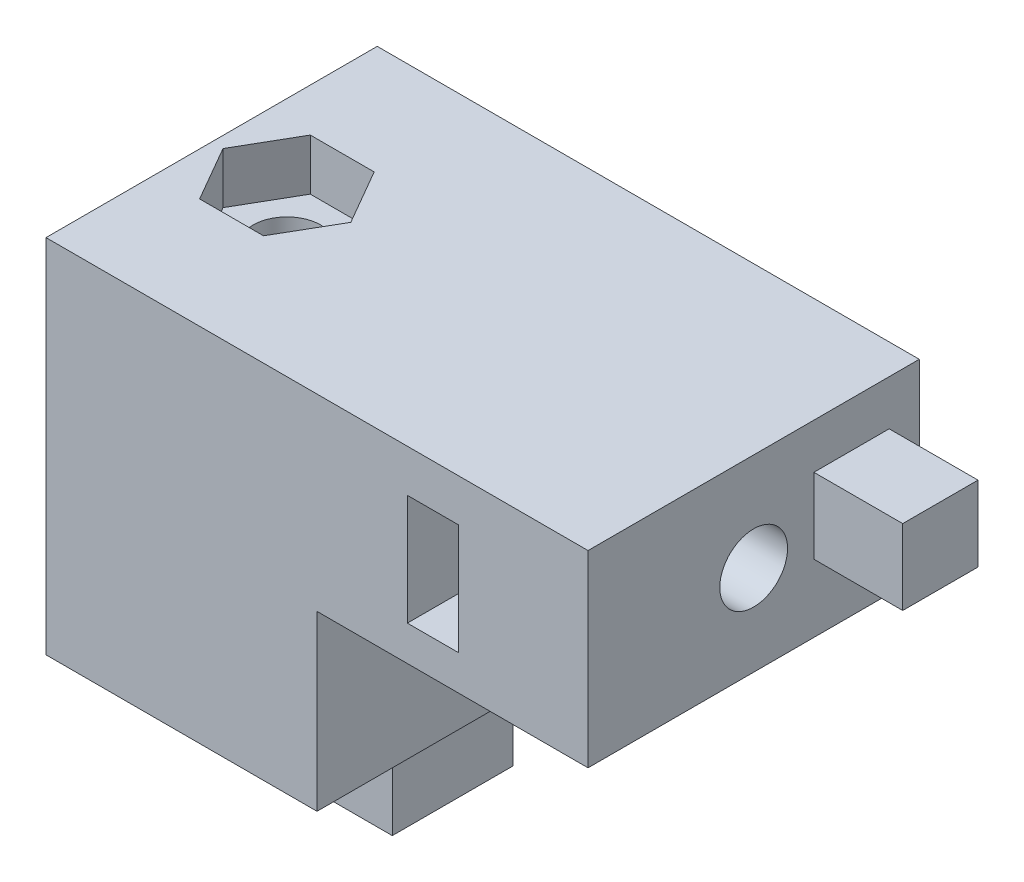
SolidWorks part; units mm, degrees
ref_plane "Спереди" through (0, 0, 0) normal (0, 0, 1) x (1, 0, 0)
ref_plane "Сверху" through (0, 0, 0) normal (0, 1, 0) x (1, 0, 0)
ref_plane "Справа" through (0, 0, 0) normal (1, 0, 0) x (0, 0, -1)
other "Configuration Table"
sketch "Профиль смещённой опоры" plane through (0, 0, 0) normal (0, 0, 1) x (1, 0, 0)
  line L0 (0, 0) -> (18, 0)
  line L1 (18, 0) -> (18, 11.5)
  line L2 (18, 11.5) -> (36, 11.5)
  line L3 (36, 11.5) -> (36, 24)
  line L4 (36, 24) -> (0, 24)
  line L5 (0, 24) -> (0, 0)
  dimension "X001" = 18
  dimension "X002" = 36
  dimension "Y001" = 11.5
  dimension "Y002" = 24
extrude "Корпус смещённой опоры" add sketch "Профиль смещённой опоры" along normal blind 22
sketch "Шип в основание — эскиз" plane through (0, 0, 0) normal (0, 1, 0) x (1, 0, 0)
  line L0 (10, -7) -> (16, -7)
  line L1 (16, -7) -> (16, -15)
  line L2 (16, -15) -> (10, -15)
  line L3 (10, -15) -> (10, -7)
  dimension "X001" = 10
  dimension "X002" = 16
  dimension "Y001" = 15
  dimension "Y002" = 7
extrude "Шип в основание" add sketch "Шип в основание — эскиз" against normal blind 5.9
sketch "Шип в заднюю стенку — эскиз" plane through (36, 0, 0) normal (1, 0, 0) x (0, 0, -1)
  line L0 (-2, 16) -> (-2, 21)
  line L1 (-2, 21) -> (-7, 21)
  line L2 (-7, 21) -> (-7, 16)
  line L3 (-7, 16) -> (-2, 16)
  dimension "X001" = 7
  dimension "X002" = 2
  dimension "Y001" = 16
  dimension "Y002" = 21
extrude "Шип в заднюю стенку" add sketch "Шип в заднюю стенку — эскиз" along normal blind 5.9
sketch "Осевой проход М4 к основанию — эскиз" plane through (0, 0, 0) normal (0, 1, 0) x (1, 0, 0)
  circle A0 centre (5, -11) radius 2.25
  dimension "Диаметр001" = 4.5
  dimension "X001" = 5
  dimension "Y001" = 11
extrude "Осевой проход М4 к основанию" cut sketch "Осевой проход М4 к основанию — эскиз" against normal through all and the other way through all
sketch "Осевой проход М4 к стенке — эскиз" plane through (36, 0, 0) normal (1, 0, 0) x (0, 0, -1)
  circle A0 centre (-11, 17.5) radius 2.25
  dimension "Диаметр001" = 4.5
  dimension "X001" = 11
  dimension "Y001" = 17.5
extrude "Осевой проход М4 к стенке" cut sketch "Осевой проход М4 к стенке — эскиз" against normal through all and the other way through all
sketch "Гнездо верхней гайки М4 — эскиз" plane through (0, 24, 0) normal (0, 1, 0) x (1, 0, 0)
  line L0 (9.2435, -11) -> (7.1218, -14.675)
  line L1 (7.1218, -14.675) -> (2.8782, -14.675)
  line L2 (2.8782, -14.675) -> (0.7565, -11)
  line L3 (0.7565, -11) -> (2.8782, -7.325)
  line L4 (2.8782, -7.325) -> (7.1218, -7.325)
  line L5 (7.1218, -7.325) -> (9.2435, -11)
  dimension "X001" = 0.7565
  dimension "X002" = 2.8782
  dimension "X003" = 7.1218
  dimension "X004" = 9.2435
  dimension "Y001" = 14.675
  dimension "Y002" = 11
  dimension "Y003" = 7.325
extrude "Гнездо верхней гайки М4" cut sketch "Гнездо верхней гайки М4 — эскиз" against normal blind 3.4
sketch "Боковая закладная гайка М4 — эскиз" plane through (0, 0, 0) normal (0, 0, 1) x (1, 0, 0)
  line L0 (24, 13.825) -> (27.4, 13.825)
  line L1 (27.4, 13.825) -> (27.4, 21.175)
  line L2 (27.4, 21.175) -> (24, 21.175)
  line L3 (24, 21.175) -> (24, 13.825)
  dimension "X001" = 24
  dimension "X002" = 27.4
  dimension "Y001" = 13.825
  dimension "Y002" = 21.175
extrude "Боковая закладная гайка М4" cut sketch "Боковая закладная гайка М4 — эскиз" against normal through all and the other way through all
equation "\"Глубина опоры\" = 35.9999999999924"
equation "\"Ширина опоры\" = 22"
equation "\"X001@Профиль смещённой опоры\" = (1*(18))"
equation "\"X002@Профиль смещённой опоры\" = (1*(\"Глубина опоры\"))"
equation "\"Y001@Профиль смещённой опоры\" = (1*(11.5))"
equation "\"Y002@Профиль смещённой опоры\" = (1*(24))"
equation "\"D1@Корпус смещённой опоры\" = \"Ширина опоры\""
